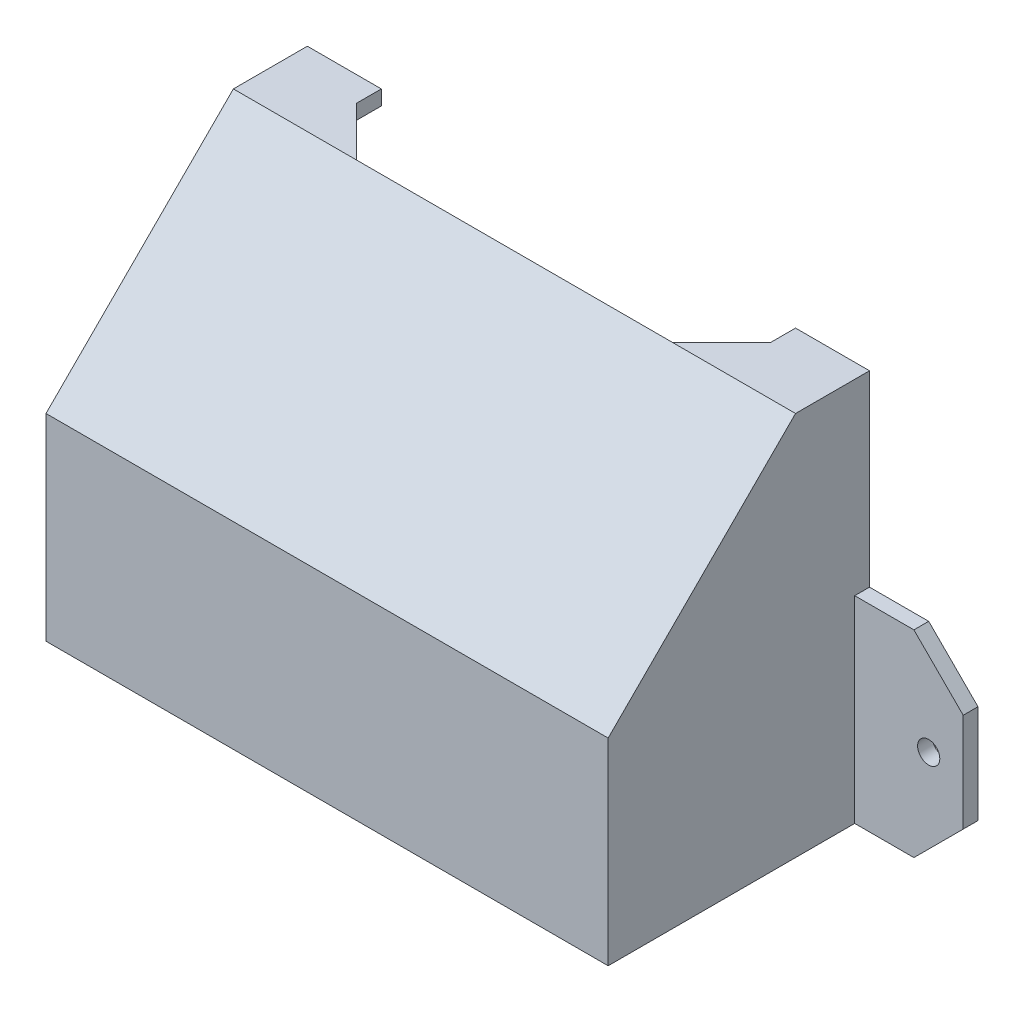
SolidWorks part; units mm, degrees
ref_plane "Front Plane" through (0, 0, 0) normal (0, 0, 1) x (1, 0, 0)
ref_plane "Top Plane" through (0, 0, 0) normal (0, 1, 0) x (1, 0, 0)
ref_plane "Right Plane" through (0, 0, 0) normal (1, 0, 0) x (0, 0, -1)
sketch "Sketch1" plane through (0, 0, 0) normal (0, 1, 0) x (1, 0, 0)
  line L0 (-54, 0) -> (-54, -50)
  line L1 (-54, -50) -> (54, -50)
  line L3 (57, -53) -> (-57, -53)
  line L4 (-57, -53) -> (-57, -3)
  line L5 (-57, 0) -> (-54, 0)
  line L6 (-57, 0) -> (-79, 0)
  line L7 (-79, 0) -> (-79, -3)
  line L8 (-79, -3) -> (-57, -3)
  line L9 (79, -3) -> (57, -3)
  line L10 (79, 0) -> (79, -3)
  line L11 (57, 0) -> (79, 0)
  line L12 (57, 0) -> (54, 0)
  line L13 (57, -53) -> (57, -3)
  line L14 (54, 0) -> (54, -50)
  dimension "D1" = 3
  dimension "D3" = 57
  dimension "D4" = 50
  dimension "D5" = 3
  dimension "D6" = 22
extrude "Boss-Extrude1" add sketch "Sketch1" along normal blind 40
sketch "Sketch2" plane through (-57, 0, 0) normal (-1, 0, 0) x (0, 0, 1)
  line L0 (53, 40) -> (15, 78)
  line L1 (15, 78) -> (0, 78)
  line L2 (0, 78) -> (0, 40)
  line L3 (0, 40) -> (53, 40)
  dimension "D1" = 45
  dimension "D2" = 15
extrude "Boss-Extrude2" add sketch "Sketch2" against normal blind 3
mirror "Mirror1" about plane through (0, 0, 0) normal (1, 0, 0) of "Boss-Extrude2"
sketch "Sketch3" plane through (54, 0, 0) normal (-1, 0, 0) x (0, 0, 1)
  line L0 (0, 78) -> (15, 78)
  line L1 (15, 78) -> (53, 40)
  line L2 (53, 40) -> (15, 78) construction
extrude "Extrude-Thin1" add sketch "Sketch3" along normal up to next thin
sketch "Sketch4" plane through (0, 78, 0) normal (0, 1, 0) x (1, 0, 0)
  line L0 (-42, 0) -> (-42, -5)
  line L1 (57, 0) -> (-57, 0) construction
  line L2 (57, -15) -> (-57, -15) construction
  line L3 (-32, -15) -> (32, -15)
  line L4 (42, -5) -> (42, 0)
  line L5 (-57, -15) -> (-57, 0) construction
  line L6 (57, -15) -> (57, 0) construction
  line L7 (-42, -5) -> (-32, -15)
  line L8 (32, -15) -> (42, -5)
  point P1 (-42, -15)
  point P7 (42, -15)
  dimension "D1" = 15
  dimension "D2" = 15
extrude "Cut-Extrude1" cut sketch "Sketch4" against normal blind 12 and the other way through all
chamfer "Chamfer1" distance 10 angle 45 4 edges at (79, 0, 1.5) (79, 40, 1.5) (-79, 0, 1.5) (-79, 40, 1.5)
sketch "Sketch5" plane through (0, 0, 3) normal (0, 0, 1) x (1, 0, 0)
  line L0 (-57, 40) -> (-57, 0) construction
  circle A0 centre (-72, 20) radius 2.25
  point P4 (-57, 20)
  dimension "D1" = 4.5
  dimension "D2" = 15
extrude "Cut-Extrude2" cut sketch "Sketch5" against normal blind 3
mirror "Mirror2" about plane through (0, 0, 0) normal (1, 0, 0) of "Cut-Extrude2"
